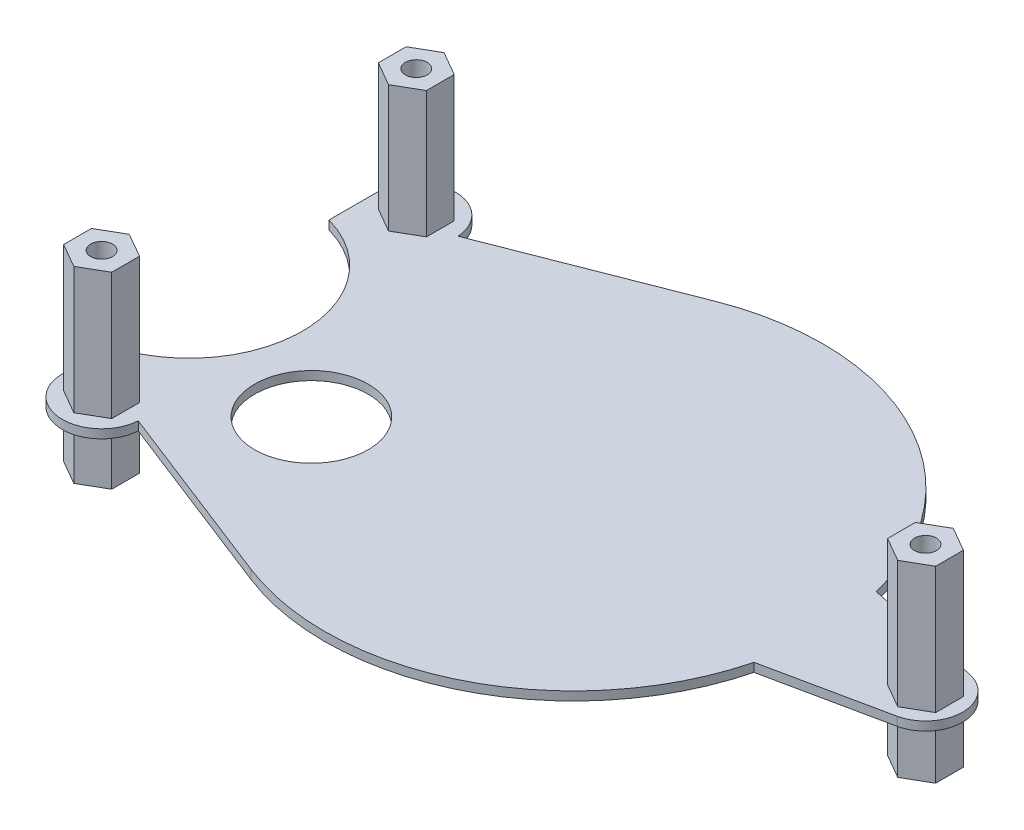
SolidWorks part; units mm, degrees
ref_plane "Front Plane" through (0, 0, 0) normal (0, 0, 1) x (1, 0, 0)
ref_plane "Top Plane" through (0, 0, 0) normal (0, 1, 0) x (1, 0, 0)
ref_plane "Right Plane" through (0, 0, 0) normal (1, 0, 0) x (0, 0, -1)
sketch "Sketch1" plane through (0, 0, 0) normal (0, 1, 0) x (1, 0, 0)
  line L0 (-22, 0) -> (22, 0) construction
  line L1 (-26.5455, 11.6443) -> (11.6364, 26.5489)
  line L2 (-26.5455, -11.6443) -> (11.6364, -26.5489)
  line L3 (-14, 18) -> (-14, -18) construction
  line L4 (-18.5, 18) -> (-18.5, 12.52)
  line L5 (-18.5, -18) -> (-18.5, -12.52)
  line L6 (22, 0) -> (62.25, 0) construction
  line L7 (49.627, 7) -> (49.627, -7) construction
  line L8 (49.627, 7) -> (63.1254, 4.1589)
  line L9 (49.627, -7) -> (63.1254, -4.1589)
  circle A0 centre (22, 0) radius 28.5
  circle A1 centre (-22, 0) radius 12.5
  circle A2 centre (-14, -18) radius 4.5
  circle A3 centre (-14, -18) radius 4.5 construction
  circle A4 centre (-14, 18) radius 4.5 construction
  circle A5 centre (-14, 18) radius 4.5
  arc A6 (-23.2192, 12.9427) -> (-23.2192, -12.9427) centre (-22, 0) cw
  circle A7 centre (62.25, 0) radius 4.25
  circle A8 centre (0, -8) radius 6.5
  point P4 (0, 0)
  point P16 (-14, 0)
  point P17 (-22, 0)
  point P29 (49.627, 0)
  dimension "D1" = 57
  dimension "D2" = 25
  dimension "D4" = 9
  dimension "D6" = 9
  dimension "D8" = 13
  dimension "D9" = 40.25
  dimension "D10" = 8.5
  dimension "D12" = 13
  dimension "D3" = 8
  dimension "D5" = 36
  dimension "D7" = 44
  dimension "D11" = 14
  dimension "D13" = 8
extrude "Boss-Extrude1" add sketch "Sketch1" along normal blind 1 contours A2 L2 L5 | L2 A2 | A8 A0 L1 A5 L4 A6 L5 L2 A2 | L2 A2 | A5 L1 | A5 L1 | L1 A5 L4 | A8 A0 | A7 L8 A0 L9 | A7 L2
sketch "Sketch2" plane through (0, 1, 0) normal (0, 1, 0) x (1, 0, 0)
  line L0 (0, 0) -> (66.5, 0) construction
  line L1 (-11.25, 16.4123) -> (-11.25, 19.5877)
  line L2 (-11.25, 19.5877) -> (-14, 21.1754)
  line L3 (-14, 21.1754) -> (-16.75, 19.5877)
  line L4 (-16.75, 19.5877) -> (-16.75, 16.4123)
  line L5 (-16.75, 16.4123) -> (-14, 14.8246)
  line L6 (-14, 14.8246) -> (-11.25, 16.4123)
  line L7 (-14, -14.8246) -> (-11.25, -16.4123)
  line L8 (-16.75, -16.4123) -> (-14, -14.8246)
  line L9 (-16.75, -19.5877) -> (-16.75, -16.4123)
  line L10 (-14, -21.1754) -> (-16.75, -19.5877)
  line L11 (-11.25, -19.5877) -> (-14, -21.1754)
  line L12 (-11.25, -16.4123) -> (-11.25, -19.5877)
  line L14 (65, 1.5877) -> (62.25, 3.1754)
  line L15 (62.25, 3.1754) -> (59.5, 1.5877)
  line L16 (59.5, 1.5877) -> (59.5, -1.5877)
  line L17 (59.5, -1.5877) -> (62.25, -3.1754)
  line L18 (62.25, -3.1754) -> (65, -1.5877)
  line L19 (65, -1.5877) -> (65, 1.5877)
  circle A0 centre (-14, 18) radius 2.75 construction
  arc A2 (63.1254, -4.1589) -> (63.1254, 4.1589) centre (62.25, 0) ccw construction
  circle A3 centre (-14, -18) radius 2.75 construction
  circle A4 centre (62.25, 0) radius 2.75 construction
  dimension "D1" = 5.5
  dimension "D2" = 5.5
extrude "Boss-Extrude2" add sketch "Sketch2" along normal blind 14.5 and the other way blind 7
hole_wizard "M3 Tapped Hole1" positions "Sketch3" profile "Sketch4" tap size "M3" standard "DIN"
sketch "Sketch3" plane through (0, 15.5, 0) normal (0, 1, 0) x (1, 0, 0)
  line L1 (-16.75, -16.4123) -> (-16.75, -19.5877) construction
  circle A0 centre (62.25, 0) radius 2.75 construction
  circle A1 centre (-14, -18) radius 2.75 construction
  point P0 (-14, 18)
  point P3 (62.25, 0)
  point P18 (-14, -18)
  point P33 (-16.75, -18)
  dimension "D1" = 5.5
  dimension "D2" = 5.5
sketch "Sketch4" plane through (-14, 15.5, -18) normal (1, 0, 0) x (0, 0, 1)
  line L0 (0, 0) -> (0, 8.2511)
  line L1 (0, 8.2511) -> (1.25, 7.5)
  line L2 (1.25, 7.5) -> (1.25, 0)
  line L5 (1.25, 0) -> (0, 0)
  line L10 (0, 8.2511) -> (-1.25, 7.5) construction
  line L11 (0, -6.35) -> (0, 107.95) construction
  dimension "Tap Drill Dia." = 2.5
  dimension "Tap Drill Depth" = 7.5
  dimension "Drill Angle" = 118
cosmetic thread "Hole Thread1" parameters "D1"=6, "D2"=3
cosmetic thread "Hole Thread3" parameters "D1"=6, "D2"=3
cosmetic thread "Hole Thread4" parameters "D1"=6, "D2"=3
ref_plane "Plane1" through (0, 4.75, 0) normal (0, 1, 0) x (1, 0, 0)
mirror "Mirror2" about plane through (0, 4.75, 0) normal (0, 1, 0) of "M3 Tapped Hole1"
cosmetic thread "Hole Thread5" parameters "D1"=6, "D2"=3
cosmetic thread "Hole Thread6" parameters "D1"=6, "D2"=3
cosmetic thread "Hole Thread7" parameters "D1"=6, "D2"=3
